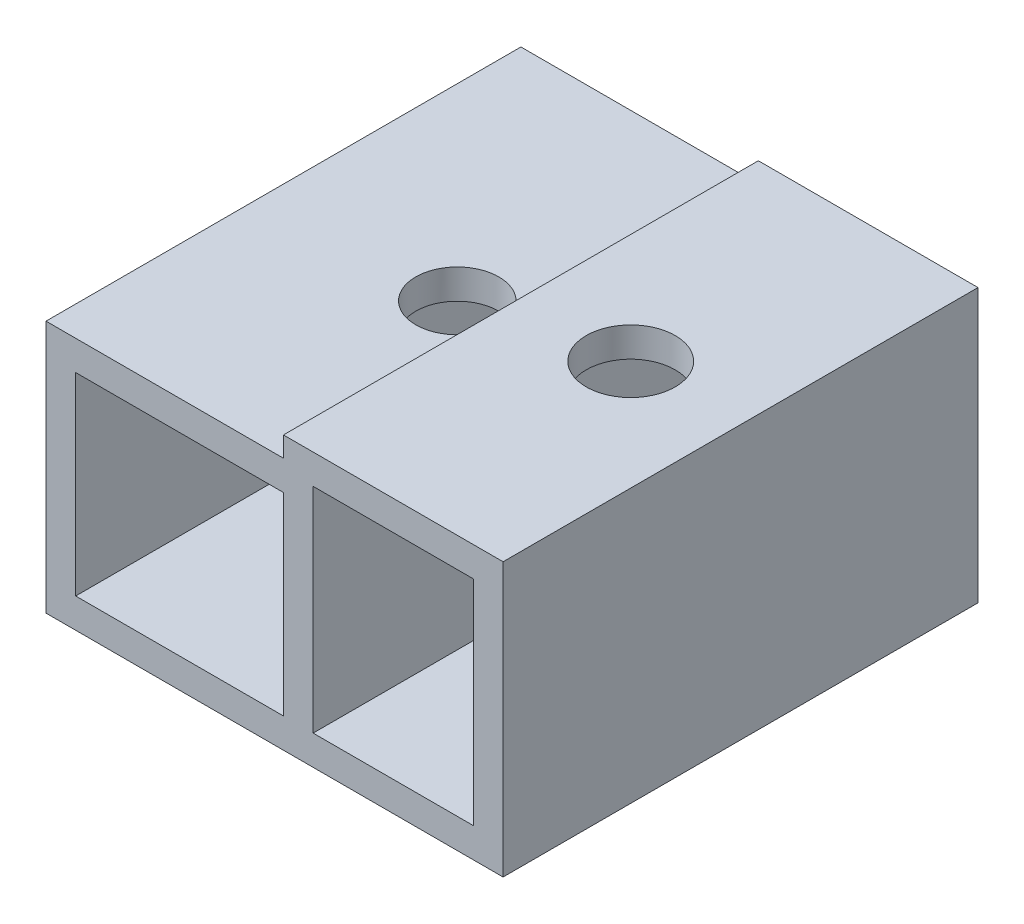
SolidWorks part; units mm, degrees
ref_plane "Front Plane" through (0, 0, 0) normal (0, 0, 1) x (1, 0, 0)
ref_plane "Top Plane" through (0, 0, 0) normal (0, 1, 0) x (1, 0, 0)
ref_plane "Right Plane" through (0, 0, 0) normal (1, 0, 0) x (0, 0, -1)
sketch "Sketch1" plane through (0, 0, 0) normal (0, 0, 1) x (1, 0, 0)
  line L0 (0, 0) -> (97.79, 0)
  line L1 (97.79, 0) -> (97.79, 58.42)
  line L2 (97.79, 58.42) -> (50.8, 58.42)
  line L3 (50.8, 58.42) -> (50.8, 54.102)
  line L4 (50.8, 54.102) -> (0, 54.102)
  line L5 (0, 54.102) -> (0, 0)
  line L6 (97.79, 0) -> (97.79, 6.35)
  line L8 (50.8, 47.752) -> (6.35, 47.752)
  line L9 (6.35, 47.752) -> (6.35, 6.35)
  line L10 (6.35, 6.35) -> (50.8, 6.35)
  line L11 (6.35, 6.35) -> (6.35, 47.752)
  line L13 (91.44, 52.07) -> (57.15, 52.07)
  line L14 (91.44, 52.07) -> (91.44, 6.35)
  line L15 (91.44, 6.35) -> (57.15, 6.35)
  line L16 (57.15, 6.35) -> (57.15, 52.07)
  line L20 (50.8, 6.35) -> (50.8, 47.752)
  dimension "D1" = 58.42
  dimension "D2" = 46.99
  dimension "D3" = 50.8
  dimension "D4" = 54.102
  dimension "D5" = 6.35
  dimension "D8" = 6.35
  dimension "D11" = 6.35
extrude "Boss-Extrude1" add sketch "Sketch1" along normal blind 101.6
sketch "Sketch2" plane through (0, 58.42, 0) normal (0, 1, 0) x (1, 0, 0)
  circle A0 centre (74.295, -50.8) radius 9.525
  dimension "D1" = 19.05
extrude "Cut-Extrude1" cut sketch "Sketch2" against normal blind 12.7
sketch "Sketch3" plane through (0, 54.102, 0) normal (0, 1, 0) x (1, 0, 0)
  line L0 (50.8, 0) -> (40.2406, 0)
  line L2 (50.8, 0) -> (0, 0) construction
  circle A0 centre (40.2406, -53.848) radius 8.89
  dimension "D2" = 17.78
  dimension "D1" = 53.848
extrude "Cut-Extrude2" cut sketch "Sketch3" against normal blind 12.7 contours A0
sketch "Sketch4" plane through (0, 6.35, 0) normal (0, 1, 0) x (1, 0, 0)
  circle A0 centre (40.132, -53.848) radius 8.5725
  dimension "D3" = 17.145
extrude "Cut-Extrude3" cut sketch "Sketch4" against normal blind 12.7
sketch "Sketch5" plane through (0, 6.35, 0) normal (0, 1, 0) x (1, 0, 0)
  line L0 (40.132, -53.848) -> (18.1356, -53.848)
  line L1 (18.1356, -53.848) -> (18.1356, -66.8528)
  line L2 (18.1356, -66.8528) -> (62.1284, -66.8528)
  line L3 (40.132, -53.848) -> (40.132, -28.8544)
  dimension "D1" = 21.9964
  dimension "D2" = 13.0048
  dimension "D3" = 43.9928
  dimension "D4" = 24.9936
